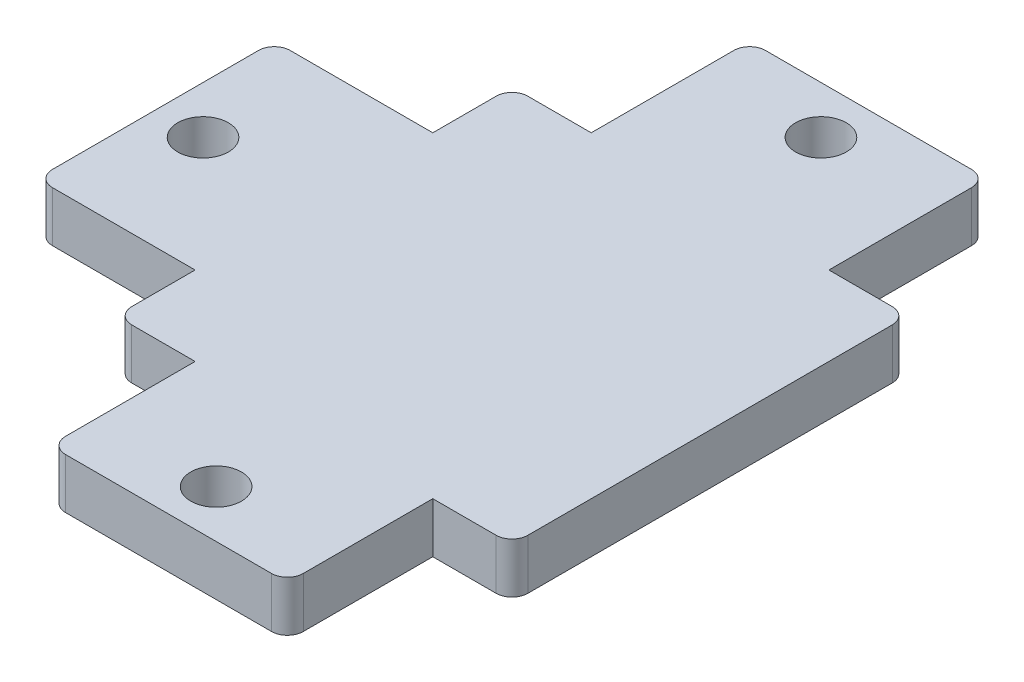
SolidWorks part; units mm, degrees
ref_plane "Front Plane" through (0, 0, 0) normal (0, 0, 1) x (1, 0, 0)
ref_plane "Top Plane" through (0, 0, 0) normal (0, 1, 0) x (1, 0, 0)
ref_plane "Right Plane" through (0, 0, 0) normal (1, 0, 0) x (0, 0, -1)
sketch "Sketch1" plane through (0, 0, 0) normal (0, 1, 0) x (1, 0, 0)
  line L1 (20, 20) -> (-20, 20)
  line L2 (20, 20) -> (20, -20)
  line L3 (20, -20) -> (-20, -20)
  line L4 (-20, 20) -> (-20, -20)
  line L5 (20, 20) -> (-20, -20) construction
  line L6 (20, -20) -> (-20, 20) construction
  point P0 (0, 0)
  dimension "D1" = 40
  dimension "D2" = 40
extrude "Boss-Extrude1" add sketch "Sketch1" along normal blind 3.175
sketch "Sketch3" plane through (0, 3.175, 0) normal (0, 1, 0) x (1, 0, 0)
  line L0 (-20, 10) -> (20, 10) construction
  line L1 (-20, 20) -> (-20, -20) construction
  line L2 (20, -20) -> (20, 20) construction
  line L3 (20, 20) -> (-20, 20) construction
  line L5 (-20, 10) -> (-5, 10)
  line L6 (-20, 10) -> (-20, 20)
  line L7 (-20, 20) -> (-5, 20)
  line L8 (-5, 10) -> (-5, 20)
  line L9 (-20, 10) -> (-5, 20) construction
  line L10 (-20, 20) -> (-5, 10) construction
  line L11 (20, 10) -> (10, 10)
  line L12 (20, 10) -> (20, 20)
  line L13 (20, 20) -> (10, 20)
  line L14 (10, 10) -> (10, 20)
  line L15 (20, 10) -> (10, 20) construction
  line L16 (20, 20) -> (10, 10) construction
  point P11 (-12.5, 15)
  point P15 (15, 15)
  dimension "D1" = 10
  dimension "D2" = 15
  dimension "D3" = 10
extrude "Cut-Extrude2" cut sketch "Sketch3" against normal blind 10
sketch "Sketch4" plane through (0, 3.175, 0) normal (0, 1, 0) x (1, 0, 0)
  line L0 (-5, 17) -> (10, 17) construction
  line L1 (-5, 10) -> (-5, 20) construction
  line L2 (10, 20) -> (10, 10) construction
  line L3 (10, 20) -> (-5, 20) construction
  circle A0 centre (2.5, 17) radius 1.6
  dimension "D2" = 3.2
  dimension "D1" = 3
extrude "Cut-Extrude3" cut sketch "Sketch4" against normal through all
sketch "Sketch5" plane through (0, 3.175, 0) normal (0, 1, 0) x (1, 0, 0)
  line L0 (-10, 10) -> (-10, -20) construction
  line L1 (-20, 10) -> (-5, 10) construction
  line L2 (-20, -20) -> (20, -20) construction
  line L3 (-20, 10) -> (-20, -20) construction
  line L4 (20, -20) -> (20, 10) construction
  line L5 (-20, 10) -> (-10, 10)
  line L6 (-20, 10) -> (-20, 5)
  line L7 (-20, 5) -> (-10, 5)
  line L8 (-10, 10) -> (-10, 5)
  line L9 (-20, 10) -> (-10, 5) construction
  line L10 (-20, 5) -> (-10, 10) construction
  line L11 (-10, -20) -> (-20, -20)
  line L12 (-10, -20) -> (-10, -10) construction
  line L13 (-10, -10) -> (-20, -10)
  line L14 (-20, -20) -> (-20, -10)
  line L15 (-10, -20) -> (-20, -10) construction
  line L16 (-10, -10) -> (-20, -20) construction
  line L17 (-10, -20) -> (20, -20)
  line L18 (-10, -20) -> (-10, -15) construction
  line L19 (-10, -15) -> (20, -15)
  line L20 (20, -20) -> (20, -15)
  line L21 (-10, -20) -> (20, -15) construction
  line L22 (-10, -15) -> (20, -20) construction
  line L23 (-10, -15) -> (-10, -10)
  point P11 (-15, 7.5)
  point P16 (-15, -15)
  point P20 (5, -17.5)
  dimension "D1" = 10
  dimension "D2" = 10
  dimension "D3" = 5
  dimension "D4" = 5
extrude "Cut-Extrude4" cut sketch "Sketch5" against normal blind 10
sketch "Sketch7" plane through (0, 3.175, 0) normal (0, 1, 0) x (1, 0, 0)
  line L0 (-20, -2.5) -> (20, -2.5) construction
  line L1 (-20, 5) -> (-20, -10) construction
  line L2 (20, -15) -> (20, 10) construction
  circle A0 centre (-17, -2.5) radius 1.6
  dimension "D2" = 3.2
  dimension "D1" = 3
extrude "Cut-Extrude6" cut sketch "Sketch7" against normal blind 10
sketch "Sketch8" plane through (0, 3.175, 0) normal (0, 1, 0) x (1, 0, 0)
  line L0 (-10, -15) -> (20, -15) construction
  line L1 (10, 10) -> (-5, 10)
  line L2 (10, 10) -> (10, -24.175)
  line L3 (10, -24.175) -> (-5, -24.175)
  line L4 (-5, 10) -> (-5, -24.175)
  line L5 (10, 10) -> (-5, -24.175) construction
  line L6 (10, -24.175) -> (-5, 10) construction
  point P4 (2.5, -7.0875)
  dimension "D1" = 9.175
  dimension "D2" = 15
extrude "Boss-Extrude2" add sketch "Sketch8" against normal up to surface (3.175 mm away) up to face at (-17, 0, 0.9)
sketch "Sketch9" plane through (0, 3.175, 0) normal (0, 1, 0) x (1, 0, 0)
  line L0 (-5, -21.175) -> (10, -21.175) construction
  line L1 (10, -24.175) -> (10, -15) construction
  line L2 (-5, -24.175) -> (10, -24.175) construction
  line L3 (-5, -15) -> (-5, -24.175) construction
  circle A0 centre (2.5, -21.175) radius 1.6
  point P8 (-5, -21.175)
  dimension "D2" = 3.2
  dimension "D1" = 3
extrude "Cut-Extrude7" cut sketch "Sketch9" against normal through all
sketch "Sketch10" plane through (0, 3.175, 0) normal (0, 1, 0) x (1, 0, 0)
  line L0 (20, -15) -> (10, -15) construction
  line L1 (20, 10) -> (15, 10)
  line L2 (20, 10) -> (20, -15)
  line L3 (20, -15) -> (15, -15)
  line L4 (15, 10) -> (15, -15)
  line L5 (20, 10) -> (15, -15) construction
  line L6 (20, -15) -> (15, 10) construction
  point P4 (17.5, -2.5)
  dimension "D1" = 5
extrude "Cut-Extrude8" cut sketch "Sketch10" against normal blind 10
fillet "Fillet1" radius 1 10 edges at (-5, 1.5875, 24.175) (10, 1.5875, 24.175) (15, 1.5875, 15) (15, 1.5875, -10) (-10, 1.5875, -10) (-10, 1.5875, 15) (-20, 1.5875, 10) (-20, 1.5875, -5) (-5, 1.5875, -20) (10, 1.5875, -20)
